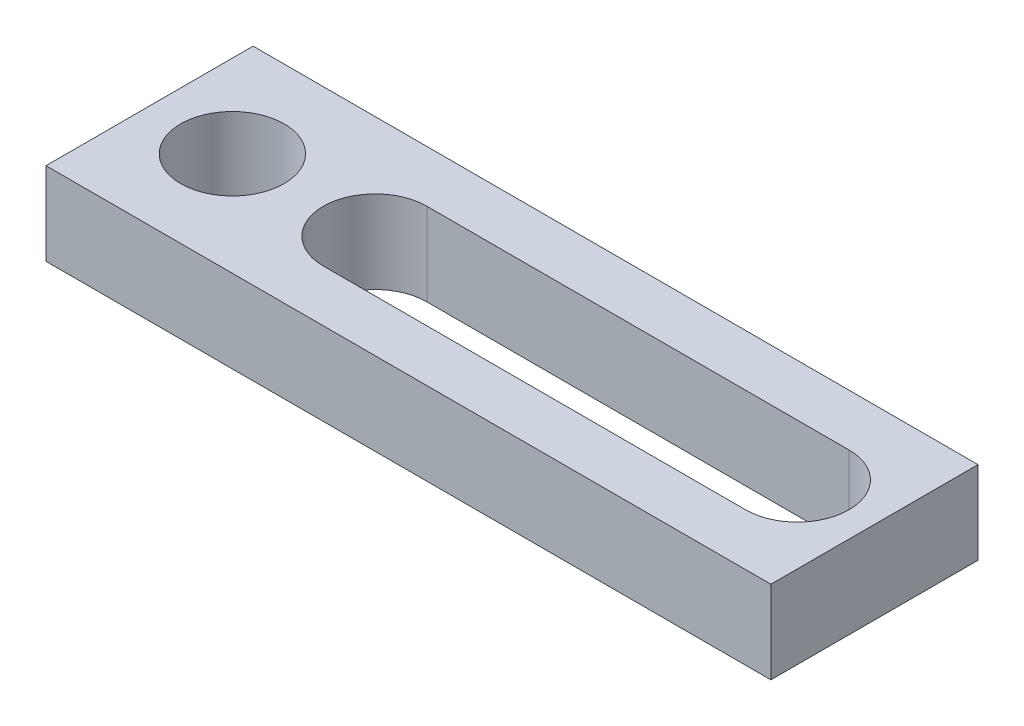
SolidWorks part; units mm, degrees
ref_plane "Front Plane" through (0, 0, 0) normal (0, 0, 1) x (1, 0, 0)
ref_plane "Top Plane" through (0, 0, 0) normal (0, 1, 0) x (1, 0, 0)
ref_plane "Right Plane" through (0, 0, 0) normal (1, 0, 0) x (0, 0, -1)
sketch "Sketch1" plane through (0, 0, 0) normal (0, 1, 0) x (1, 0, 0)
  line L0 (-24.2208, 4.2368) -> (16.5458, 4.2368) construction
  line L1 (24, 14.2368) -> (-46, 14.2368)
  line L2 (24, 14.2368) -> (24, -5.7632)
  line L3 (24, -5.7632) -> (-46, -5.7632)
  line L4 (-46, 14.2368) -> (-46, -5.7632)
  line L5 (-24.2208, 9.2368) -> (16.5458, 9.2368)
  line L6 (-24.2208, -0.7632) -> (16.5458, -0.7632)
  circle A0 centre (-38, 4.2368) radius 5
  arc A1 (-24.2208, 9.2368) -> (-24.2208, -0.7632) centre (-24.2208, 4.2368) ccw
  arc A2 (16.5458, -0.7632) -> (16.5458, 9.2368) centre (16.5458, 4.2368) ccw
  point P0 (0, 0)
  point P10 (-3.8375, 4.2368)
  point P15 (0, 0)
  dimension "D1" = 10
  dimension "10" = 70
  dimension "20" = 20
  dimension "D2" = 8
  dimension "D3" = 10
  dimension "D4" = 10
  dimension "D5" = 10
extrude "Boss-Extrude1" add sketch "Sketch1" along normal blind 8
